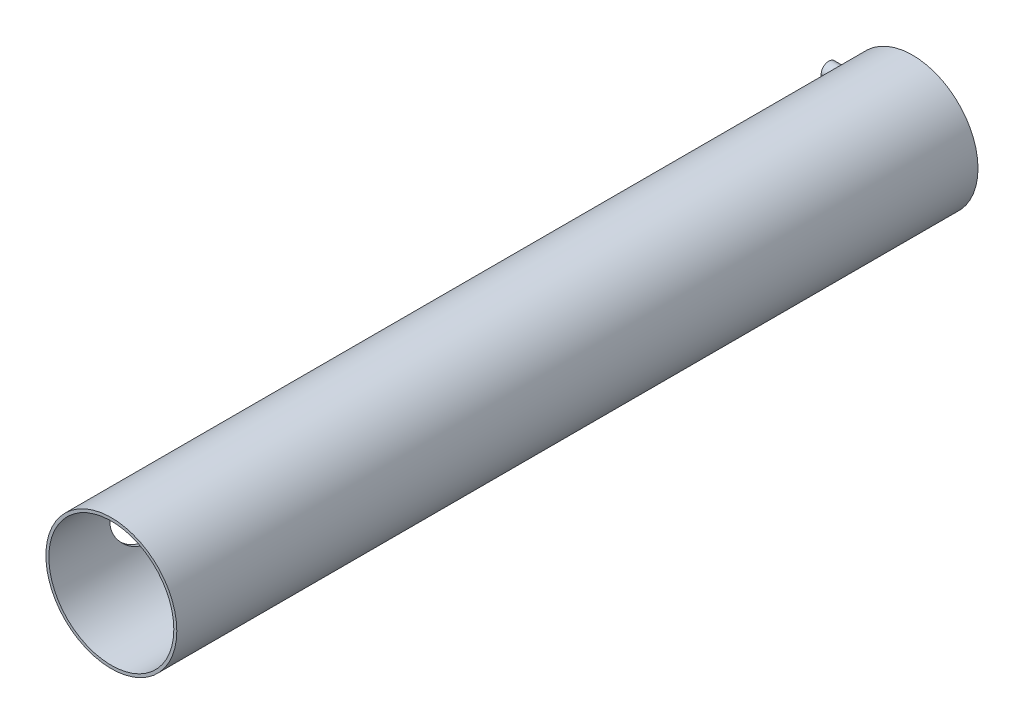
SolidWorks part; units mm, degrees
ref_plane "Front Plane" through (0, 0, 0) normal (0, 0, 1) x (1, 0, 0)
ref_plane "Top Plane" through (0, 0, 0) normal (0, 1, 0) x (1, 0, 0)
ref_plane "Right Plane" through (0, 0, 0) normal (1, 0, 0) x (0, 0, -1)
sketch "Sketch2" plane through (0, 0, 0) normal (0, 0, 1) x (1, 0, 0)
  circle A0 centre (0, 0) radius 10.3759
  dimension "D1" = 20.7518
extrude "Boss-Extrude1" add sketch "Sketch2" along normal blind 127
sketch "Sketch3" plane through (0, 0, 127) normal (0, 0, 1) x (1, 0, 0)
  circle A0 centre (0, 0) radius 9.906
  dimension "D1" = 19.812
extrude "Cut-Extrude1" cut sketch "Sketch3" against normal blind 124.46 contours A0
sketch "Sketch4" plane through (0, 0, 0) normal (1, 0, 0) x (0, 0, -1)
  line L0 (-112.6277, 0) -> (-13.5294, 0) construction
  line L1 (-112.6277, 4.696) -> (-13.5294, 4.696)
  line L2 (-112.6277, -4.696) -> (-13.5294, -4.696)
  arc A0 (-112.6277, 4.696) -> (-112.6277, -4.696) centre (-112.6277, 0) ccw
  arc A1 (-13.5294, -4.696) -> (-13.5294, 4.696) centre (-13.5294, 0) ccw
  point P2 (-63.0786, 0)
  dimension "D1" = 9.3921
  dimension "D2" = 99.0983
extrude "Cut-Extrude2" cut sketch "Sketch4" against normal blind 12.7 contours L1 A1 L2 A0
sketch "Sketch5" plane through (0, 0, 0) normal (1, 0, 0) x (0, 0, -1)
  line L0 (-1.8495, 3.5521) -> (-1.8495, -3.5521) construction
  line L1 (-0.6454, 3.5521) -> (-0.6454, -3.5521)
  line L2 (-3.0536, 3.5521) -> (-3.0536, -3.5521)
  arc A0 (-0.6454, 3.5521) -> (-3.0536, 3.5521) centre (-1.8495, 3.5521) ccw
  arc A1 (-3.0536, -3.5521) -> (-0.6454, -3.5521) centre (-1.8495, -3.5521) ccw
  point P2 (-1.8495, 0)
  dimension "D1" = 2.4082
  dimension "D2" = 7.1043
extrude "Boss-Extrude2" add sketch "Sketch5" against normal blind 11.43
